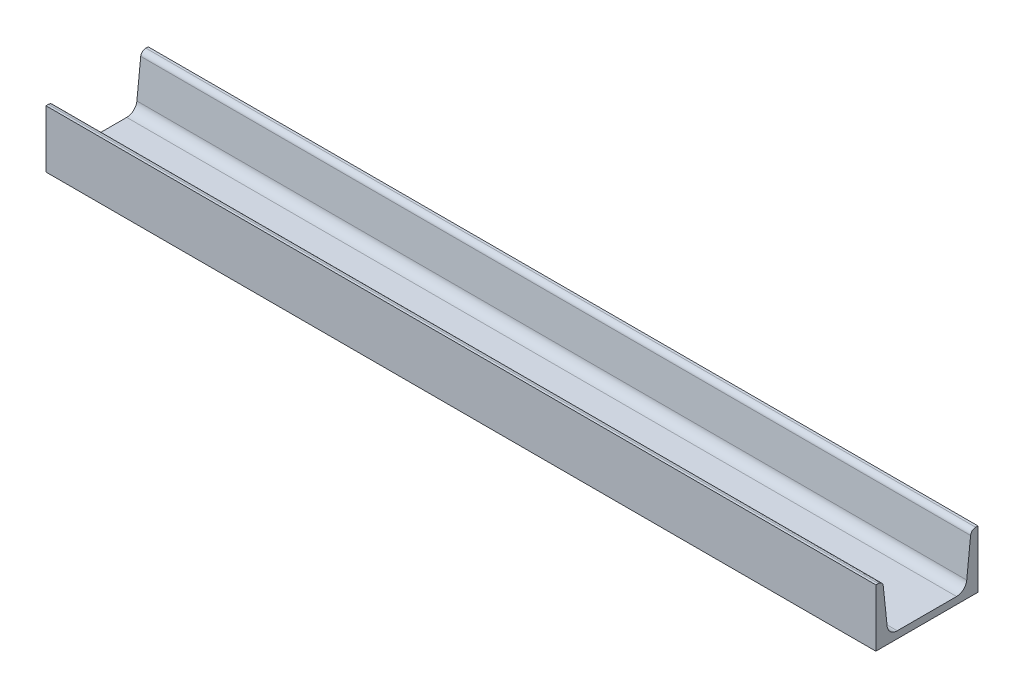
SolidWorks part; units mm, degrees
material "ASTM A36 Acero"
ref_plane "Alzado" through (0, 0, 0) normal (0, 0, 1) x (1, 0, 0)
ref_plane "Planta" through (0, 0, 0) normal (0, 1, 0) x (1, 0, 0)
ref_plane "Vista lateral" through (0, 0, 0) normal (1, 0, 0) x (0, 0, -1)
sketch "Croquis1" plane through (0, 0, 0) normal (0, 0, 1) x (1, 0, 0)
  line L0 (0, 0) -> (650, 0)
  dimension "D1" = 650
other "Canal c 80 X 8(1)"
ref_plane "Plano2" through (0, 0, 0) normal (1, 0, 0) x (0, 1, 0)
sketch "Sketch15" plane through (0, 0, 0) normal (1, 0, 0) x (0, 1, 0)
  line L0 (45, 80) -> (0, 80)
  line L1 (45, 0) -> (0, 0)
  line L2 (0, 80) -> (0, 0)
  line L6 (45, 80) -> (45, 78.1774)
  line L7 (45, 0) -> (45, 1.8226)
  line L12 (5.5, 63.221) -> (5.5, 16.779)
  line L17 (12.6638, 71.1771) -> (41.4181, 74.1993)
  line L18 (12.6638, 8.8229) -> (41.4181, 5.8007)
  arc A0 (41.4181, 74.1993) -> (45, 78.1774) centre (41, 78.1774) ccw
  arc A1 (41.4181, 5.8007) -> (45, 1.8226) centre (41, 1.8226) cw
  arc A9 (5.5, 16.779) -> (12.6638, 8.8229) centre (13.5, 16.779) ccw
  arc A10 (5.5, 63.221) -> (12.6638, 71.1771) centre (13.5, 63.221) cw
  point P8 (0, 40)
  point P9 (5.5, 40)
  point P10 (22.5, 80)
  point P11 (22.5, 0)
  point P12 (45, 5.4242)
  point P13 (45, 74.5758)
  point P14 (0, 0)
  dimension "D4" = 4
  dimension "RI" = 8
  dimension "D2" = 6
  dimension "D3" = 16.779
  dimension "Depth" = 80
  dimension "BF" = 45
  dimension "TW" = 5.5
  dimension "d1" = 46.4419
